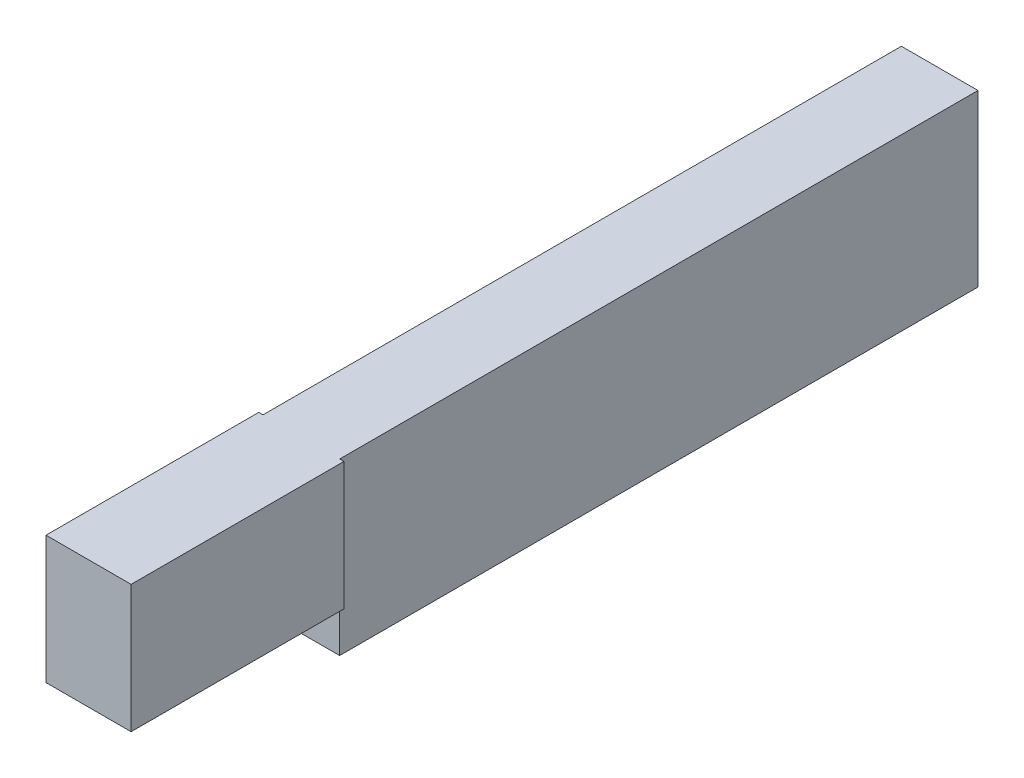
SolidWorks part; units mm, degrees
ref_plane "Front Plane" through (0, 0, 0) normal (0, 0, 1) x (1, 0, 0)
ref_plane "Top Plane" through (0, 0, 0) normal (0, 1, 0) x (1, 0, 0)
ref_plane "Right Plane" through (0, 0, 0) normal (1, 0, 0) x (0, 0, -1)
sketch "Sketch1" plane through (0, 0, 0) normal (0, 0, 1) x (1, 0, 0)
  line L1 (-2.25, -5) -> (2.25, -5)
  line L2 (-2.25, -5) -> (-2.25, 5)
  line L3 (-2.25, 5) -> (2.25, 5)
  line L4 (2.25, -5) -> (2.25, 5)
  line L5 (-2.25, -5) -> (2.25, 5) construction
  line L6 (-2.25, 5) -> (2.25, -5) construction
  point P0 (0, 0)
  dimension "D1" = 10
  dimension "D2" = 4.5
sketch "Sketch2" plane through (0, 0, 37.5) normal (0, 0, 1) x (1, 0, 0)
  line L0 (-5, -5) -> (5, -5) construction
  line L1 (-2.5, -2.5) -> (2.5, -2.5)
  line L10 (-2.5, -2.5) -> (-2.5, 5)
  line L11 (5, 5) -> (-5, 5) construction
  line L12 (-2.5, 5) -> (2.5, 5)
  line L13 (2.5, 5) -> (2.5, -2.5)
  point P0 (0, 0)
  dimension "D1" = 2.5
sketch "Sketch3" plane through (0, 0, 37.5) normal (0, 0, 1) x (1, 0, 0)
extrude "Boss-Extrude2" add sketch "Sketch2" along normal blind 12.5
extrude "Boss-Extrude4" add sketch "Sketch1" along normal blind 37.5
